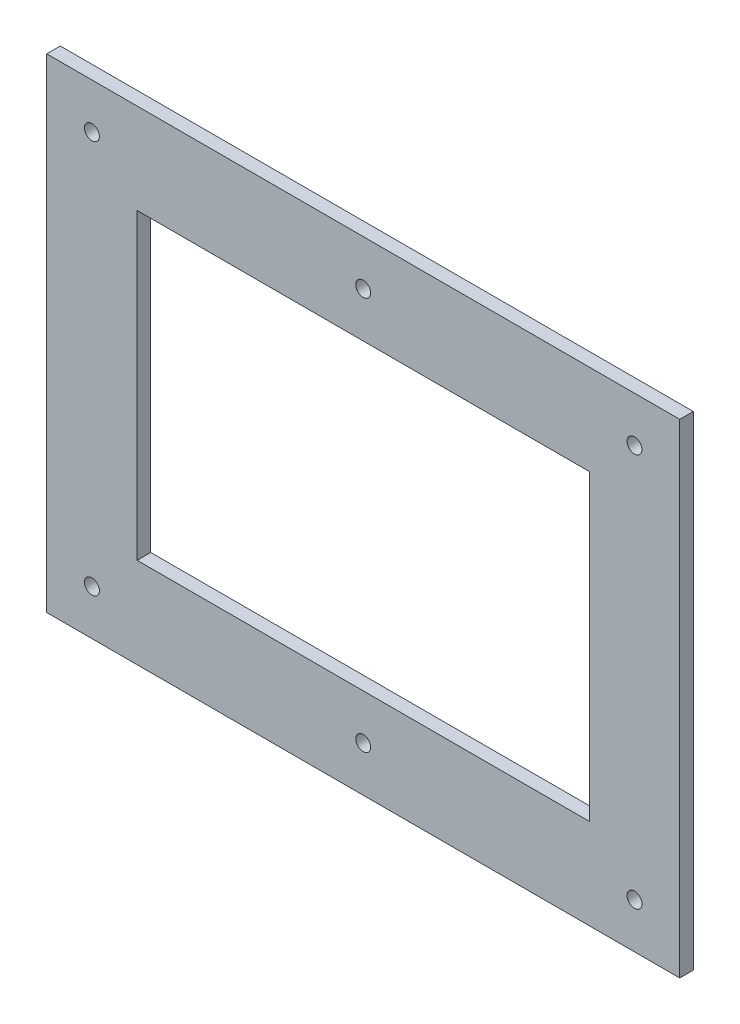
SolidWorks part; units mm, degrees
ref_plane "Plan de face" through (0, 0, 0) normal (0, 0, 1) x (1, 0, 0)
ref_plane "Plan de dessus" through (0, 0, 0) normal (0, 1, 0) x (1, 0, 0)
ref_plane "Plan de droite" through (0, 0, 0) normal (1, 0, 0) x (0, 0, -1)
sketch "Esquisse1" plane through (0, 0, 0) normal (0, 0, 1) x (1, 0, 0)
  line L0 (-20, 87) -> (0, 67) construction
  line L1 (0, 0) -> (100, 0)
  line L2 (0, 0) -> (0, 67)
  line L3 (0, 67) -> (100, 67)
  line L4 (100, 0) -> (100, 67)
  line L5 (-20, 87) -> (120, 87)
  line L6 (-20, 87) -> (-20, -20)
  line L7 (-20, -20) -> (120, -20)
  line L8 (120, 87) -> (120, -20)
  line L9 (100, 67) -> (120, 87) construction
  line L10 (100, 0) -> (120, -20) construction
  line L11 (0, 0) -> (-20, -20) construction
  line L12 (110, 77) -> (-10, 77) construction
  line L13 (-10, 77) -> (-10, -10) construction
  line L14 (-10, -10) -> (110, -10) construction
  line L15 (110, -10) -> (110, 77) construction
  line L16 (100, 33.5) -> (0, 33.5) construction
  line L17 (3, 51.1933) -> (3, 11.8866) construction
  line L18 (97, 11.8866) -> (97, 51.1933) construction
  circle A0 centre (97, 33.5) radius 1.5 construction
  circle A1 centre (3, 33.5) radius 1.5 construction
  circle A2 centre (110, 77) radius 1.65
  circle A3 centre (-10, 77) radius 1.65
  circle A4 centre (-10, -10) radius 1.65
  circle A5 centre (110, -10) radius 1.65
  circle A6 centre (50, 77) radius 1.65
  circle A7 centre (50, -10) radius 1.65
  point P9 (50, -20)
  dimension "D9" = 3
  dimension "D10" = 3
  dimension "D11" = 3.3
  dimension "D1" = 67
  dimension "D2" = 100
  dimension "D3" = 20
  dimension "D4" = 20
  dimension "D5" = 20
  dimension "D6" = 20
  dimension "D7" = 3
  dimension "D8" = 3
extrude "Boss.-Extru.1" add sketch "Esquisse1" along normal blind 3
